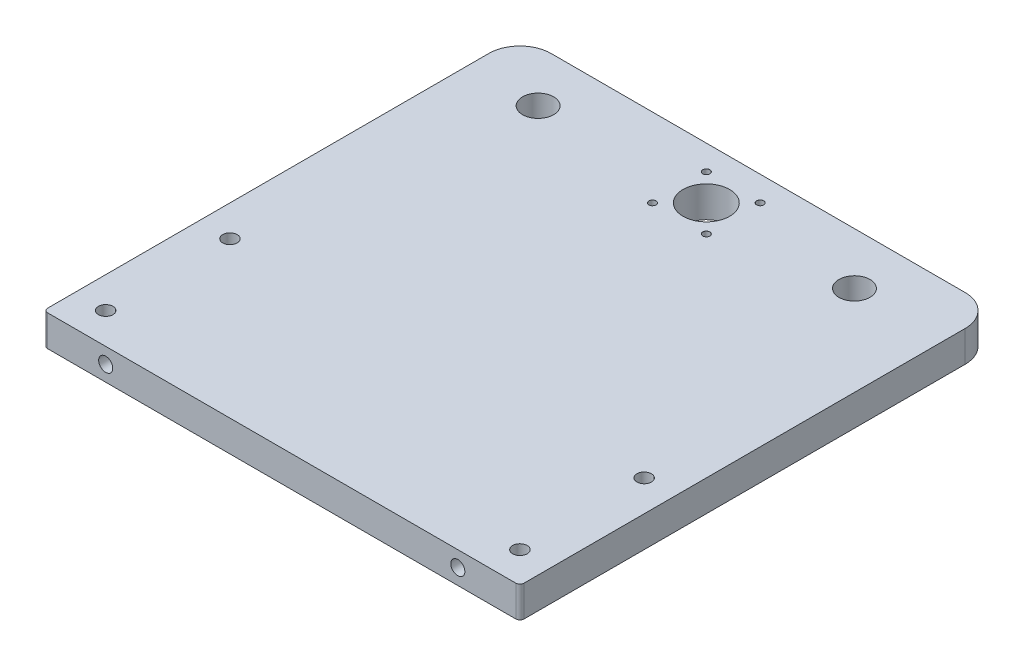
SolidWorks part; units mm, degrees
ref_plane "Vorne" through (0, 0, 0) normal (0, 0, 1) x (1, 0, 0)
ref_plane "Oben" through (0, 0, 0) normal (0, 1, 0) x (1, 0, 0)
ref_plane "Rechts" through (0, 0, 0) normal (1, 0, 0) x (0, 0, -1)
ref_plane "E_Boden" through (0, 1, 0) normal (0, 1, 0) x (1, 0, 0)
sketch "Skizze1" plane through (0, 0, 0) normal (0, 1, 0) x (1, 0, 0)
  line L0 (-170.1685, 0) -> (216.6498, 0) construction
  line L1 (0, 0) -> (0, 128.6817) construction
  line L2 (0, 128.6817) -> (0, -115.148) construction
  line L4 (-115, 115) -> (115, 115)
  line L5 (-115, 115) -> (-115, -115)
  line L6 (-115, -115) -> (115, -115)
  line L7 (115, 115) -> (115, -115)
  dimension "D1" = 230
  dimension "D2" = 230
extrude "Aufsatz-Linear austragen1" add sketch "Skizze1" along normal blind 15
hole_wizard "Ø15.0 (15) Durchmesser Bohrung1" positions "Skizze6" profile "Skizze7" hole size "Ø15.0" standard "DIN" end condition through all
sketch "Skizze6" plane through (0, 15, 0) normal (0, 1, 0) x (1, 0, 0)
  line L1 (115, 115) -> (-115, 115) construction
  point P0 (-81.223, 90)
  point P2 (71.5255, 90)
  dimension "D1" = 25
  dimension "D2" = 25
sketch "Skizze7" plane through (-81.223, 15, -90) normal (1, 0, 0) x (0, 0, 1)
  line L0 (0, 0) -> (0, 15)
  line L1 (0, 15) -> (7.5, 15)
  line L2 (7.5, 15) -> (7.5, 0)
  line L5 (7.5, 0) -> (0, 0)
  line L11 (0, -6.35) -> (0, 107.95) construction
  dimension "Bohrerdurchmesser" = 15
  dimension "Bohrungstiefe" = 15
hole_wizard "Ø3.4 (3.4) Durchmesser Bohrung1" positions "Skizze8" profile "Skizze9" hole size "Ø3.4" standard "DIN" end condition through all
sketch "Skizze8" plane through (0, 15, 0) normal (0, 1, 0) x (1, 0, 0)
  line L0 (115, 115) -> (-115, 115) construction
  line L1 (0, 71.4415) -> (0, 3.4399) construction
  line L3 (-115, 115) -> (-115, -115) construction
  line L4 (-44.1401, 90) -> (32.4162, 90) construction
  point P0 (-13, 103)
  point P2 (13, 103)
  point P4 (-13, 77)
  point P6 (13, 77)
  point P30 (0, 0)
  dimension "D2" = 26
  dimension "D3" = 26
  dimension "D4" = 115
  dimension "D5" = 25
sketch "Skizze9" plane through (-13, 15, -103) normal (1, 0, 0) x (0, 0, 1)
  line L0 (0, 0) -> (0, 15)
  line L1 (0, 15) -> (1.725, 15)
  line L2 (1.7, 14.975) -> (1.7, 0.025)
  line L3 (1.7, 0.025) -> (1.725, 0)
  line L5 (1.725, 0) -> (0, 0)
  line L6 (-1.7, 0.025) -> (-1.725, 0) construction
  line L7 (1.725, 15) -> (1.7, 14.975)
  line L8 (-1.725, 15) -> (-1.7, 14.975) construction
  line L11 (0, -6.35) -> (0, 107.95) construction
  dimension "Bohrerdurchmesser" = 3.4
  dimension "Bohrungstiefe" = 15
  dimension "Senkdurchmesser2 (Oben)" = 3.45
  dimension "Senkwinkel2 (Oben)" = 90
  dimension "Senkdurchmesser2 (Unten)" = 3.45
  dimension "Senkwinkel2 (Unten)" = 90
hole_wizard "Ø22.5 (22.5) Durchmesser Bohrung1" positions "Skizze10" profile "Skizze11" hole size "Ø22.5" standard "DIN" end condition through all
sketch "Skizze10" plane through (0, 15, 0) normal (0, 1, 0) x (1, 0, 0)
  line L0 (115, 115) -> (-115, 115) construction
  point P0 (0, 90)
  dimension "D1" = 25
sketch "Skizze11" plane through (0, 15, -90) normal (1, 0, 0) x (0, 0, 1)
  line L0 (0, 0) -> (0, 15)
  line L1 (0, 15) -> (11.25, 15)
  line L2 (11.25, 15) -> (11.25, 0)
  line L5 (11.25, 0) -> (0, 0)
  line L11 (0, -6.35) -> (0, 107.95) construction
  dimension "Bohrerdurchmesser" = 22.5
  dimension "Bohrungstiefe" = 15
hole_wizard "Ø7.0 (7) Durchmesser Bohrung1" positions "Skizze12" profile "Skizze13" hole size "Ø7.0" standard "DIN" end condition through all
sketch "Skizze12" plane through (0, 15, 0) normal (0, 1, 0) x (1, 0, 0)
  line L0 (-115, 115) -> (-115, -115) construction
  line L1 (115, -115) -> (115, 115) construction
  line L2 (-115, -115) -> (115, -115) construction
  point P0 (-100, -40)
  point P2 (-100, -100)
  point P4 (100, -40)
  point P6 (100, -100)
  point P9 (0, 0)
  point P10 (0, 0)
  point P11 (0, 0)
  point P12 (0, 0)
  point P19 (-100, -67.0087)
  dimension "D1" = 15
  dimension "D2" = 15
  dimension "D3" = 15
  dimension "D4" = 60
sketch "Skizze13" plane through (-100, 15, 40) normal (1, 0, 0) x (0, 0, 1)
  line L0 (0, 0) -> (0, 15)
  line L1 (0, 15) -> (3.5, 15)
  line L2 (3.5, 15) -> (3.5, 0)
  line L5 (3.5, 0) -> (0, 0)
  line L11 (0, -6.35) -> (0, 107.95) construction
  dimension "Bohrerdurchmesser" = 7
  dimension "Bohrungstiefe" = 15
fillet "Verrundung5" radius 15 2 edges at (115, 7.5, -115) (-115, 7.5, -115)
fillet "Verrundung6" radius 2 2 edges at (115, 7.5, 115) (-115, 7.5, 115)
hole_wizard "M8 Gewindebohrung1" positions "Skizze16" profile "Skizze17" tap size "M8" standard "DIN"
sketch "Skizze16" plane through (0, 0, 115) normal (0, 0, 1) x (1, 0, 0)
  line L0 (0, -9.8322) -> (0, 40.9109) construction
  line L5 (-132.4013, 7.5) -> (137.634, 7.5) construction
  line L7 (-113, 15) -> (113, 15) construction
  line L8 (-113, 0) -> (113, 0) construction
  point P0 (-85, 7.5)
  point P2 (85, 7.5)
  dimension "D1" = 170
sketch "Skizze17" plane through (-85, 7.5, 115) normal (1, 0, 0) x (0, -1, 0)
  line L0 (0, 0) -> (0, 32.0429)
  line L1 (0, 32.0429) -> (3.4, 30)
  line L2 (3.4, 30) -> (3.4, 0)
  line L5 (3.4, 0) -> (0, 0)
  line L10 (0, 32.0429) -> (-3.4, 30) construction
  line L11 (0, -6.35) -> (0, 107.95) construction
  dimension "Bohrerdurchmesser" = 6.8
  dimension "Bohrungstiefe" = 30
  dimension "Spitzenwinkel" = 118
cosmetic thread "Bohrungsgewinde1" parameters "D1"=16, "D2"=8
cosmetic thread "Bohrungsgewinde2" parameters "D1"=16, "D2"=8
